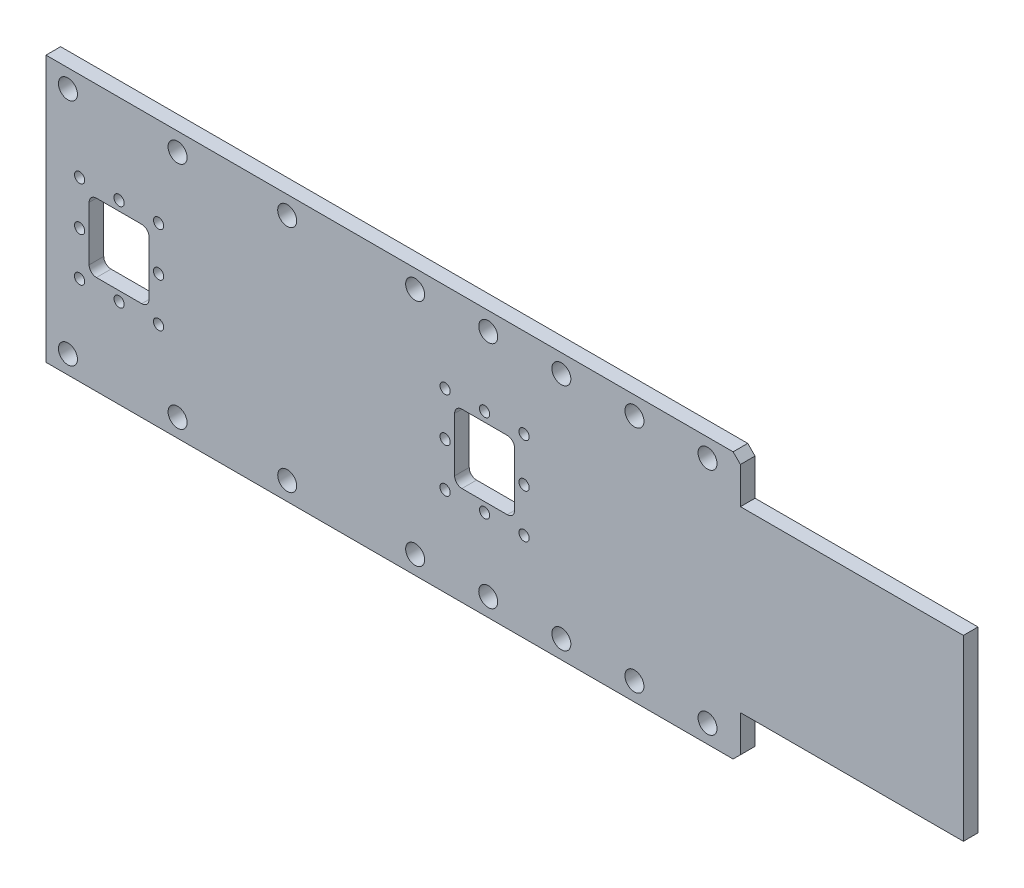
SolidWorks part; units mm, degrees
ref_plane "前视基准面" through (0, 0, 0) normal (0, 0, 1) x (1, 0, 0)
ref_plane "上视基准面" through (0, 0, 0) normal (0, 1, 0) x (1, 0, 0)
ref_plane "右视基准面" through (0, 0, 0) normal (1, 0, 0) x (0, 0, -1)
sketch "草图1" plane through (0, 0, 0) normal (0, 0, 1) x (1, 0, 0)
  line L1 (-627.5, 182) -> (627.5, 182)
  line L2 (-627.5, 182) -> (-627.5, -182)
  line L3 (-627.5, -182) -> (627.5, -182)
  line L4 (627.5, 182) -> (627.5, -182)
  line L5 (-627.5, 182) -> (627.5, -182) construction
  line L6 (-627.5, -182) -> (627.5, 182) construction
  point P0 (0, 0)
  dimension "D1" = 1255
  dimension "D2" = 364
extrude "凸台-拉伸1" add sketch "草图1" against normal blind 20
sketch "草图2" plane through (0, 0, 0) normal (0, 0, 1) x (1, 0, 0)
  line L0 (-627.5, 182) -> (-627.5, -182) construction
  line L1 (627.5, 182) -> (322.5, 182)
  line L2 (627.5, 182) -> (627.5, 122)
  line L3 (627.5, 122) -> (322.5, 122)
  line L4 (322.5, 182) -> (322.5, 122)
  line L5 (627.5, -182) -> (322.5, -182)
  line L6 (627.5, -182) -> (627.5, -122)
  line L7 (627.5, -122) -> (322.5, -122)
  line L8 (322.5, -182) -> (322.5, -122)
  point P13 (322.5, -152)
  dimension "D1" = 244
  dimension "D2" = 122
  dimension "D3" = 950
extrude "切除-拉伸1" cut sketch "草图2" against normal through all
chamfer "倒角1" distance 10 angle 45 2 edges at (322.5, -182, -10) (322.5, 182, -10)
sketch "草图3" plane through (0, 0, 0) normal (0, 0, 1) x (1, 0, 0)
  line L0 (0, 0) -> (306.6979, 0) construction
  line L2 (-627.5, 182) -> (-627.5, -182) construction
  line L3 (-58.5, 47) -> (3.5, 47)
  line L4 (-558.5, 47) -> (-496.5, 47)
  line L5 (-568.5, 37) -> (-568.5, -37)
  line L6 (-558.5, -47) -> (-496.5, -47)
  line L7 (-486.5, 37) -> (-486.5, -37)
  line L8 (-568.5, 47) -> (-486.5, -47) construction
  line L9 (-568.5, -47) -> (-486.5, 47) construction
  line L10 (-68.5, 37) -> (-68.5, -37)
  line L11 (-58.5, -47) -> (3.5, -47)
  line L12 (13.5, 37) -> (13.5, -37)
  line L13 (-68.5, 47) -> (13.5, -47) construction
  line L14 (-68.5, -47) -> (13.5, 47) construction
  line L15 (-527.5, 0) -> (-27.5, 0) construction
  circle A0 centre (-597.5, 157) radius 13
  circle A1 centre (-447.5, 157) radius 13
  circle A2 centre (-297.5, 157) radius 13
  circle A3 centre (-122.5, 157) radius 13
  circle A4 centre (-22.5, 157) radius 13
  circle A5 centre (77.5, 157) radius 13
  circle A6 centre (177.5, 157) radius 13
  circle A7 centre (277.5, 157) radius 13
  circle A8 centre (277.5, -157) radius 13
  circle A9 centre (177.5, -157) radius 13
  circle A10 centre (77.5, -157) radius 13
  circle A11 centre (-22.5, -157) radius 13
  circle A12 centre (-122.5, -157) radius 13
  circle A13 centre (-297.5, -157) radius 13
  circle A14 centre (-447.5, -157) radius 13
  circle A15 centre (-597.5, -157) radius 13
  circle A16 centre (-581.5, 60) radius 7
  circle A17 centre (-527.5, 60) radius 7
  circle A18 centre (-473.5, 60) radius 7
  circle A19 centre (-473.5, 0) radius 7
  circle A20 centre (-581.5, 0) radius 7
  circle A21 centre (-581.5, -60) radius 7
  circle A22 centre (-527.5, -60) radius 7
  circle A23 centre (-473.5, -60) radius 7
  arc A24 (-568.5, -37) -> (-558.5, -47) centre (-558.5, -37) ccw
  arc A25 (-496.5, -47) -> (-486.5, -37) centre (-496.5, -37) ccw
  arc A26 (-496.5, 47) -> (-486.5, 37) centre (-496.5, 37) cw
  arc A27 (-558.5, 47) -> (-568.5, 37) centre (-558.5, 37) ccw
  circle A28 centre (-81.5, 60) radius 7
  circle A29 centre (-27.5, 60) radius 7
  circle A30 centre (26.5, 60) radius 7
  circle A31 centre (26.5, 0) radius 7
  circle A32 centre (-81.5, 0) radius 7
  circle A33 centre (-81.5, -60) radius 7
  circle A34 centre (-27.5, -60) radius 7
  circle A35 centre (26.5, -60) radius 7
  arc A36 (-68.5, -37) -> (-58.5, -47) centre (-58.5, -37) ccw
  arc A37 (3.5, -47) -> (13.5, -37) centre (3.5, -37) ccw
  arc A38 (3.5, 47) -> (13.5, 37) centre (3.5, 37) cw
  arc A39 (-58.5, 47) -> (-68.5, 37) centre (-58.5, 37) ccw
  point P37 (-527.5, 0)
  point P42 (-27.5, 0)
  point P79 (0, 0)
  dimension "D1" = 314
  dimension "D2" = 26
  dimension "D3" = 26
  dimension "D4" = 30
  dimension "D5" = 150
  dimension "D6" = 150
  dimension "D7" = 175
  dimension "D8" = 100
  dimension "D9" = 100
  dimension "D10" = 100
  dimension "D11" = 100
  dimension "D12" = 26
  dimension "D13" = 26
  dimension "D14" = 26
  dimension "D15" = 26
  dimension "D16" = 26
  dimension "D17" = 26
  dimension "D18" = 94
  dimension "D20" = 60
  dimension "D21" = 60
  dimension "D22" = 54
  dimension "D23" = 54
  dimension "D25" = 14
  dimension "D26" = 14
  dimension "D27" = 14
  dimension "D28" = 14
  dimension "D29" = 14
  dimension "D30" = 14
  dimension "D31" = 14
  dimension "D32" = 14
  dimension "D33" = 10
  dimension "D19" = 82
  dimension "D24" = 59
  dimension "D35" = 500
  dimension "D34" = 2
extrude "切除-拉伸2" cut sketch "草图3" against normal up to next (20 mm away)
